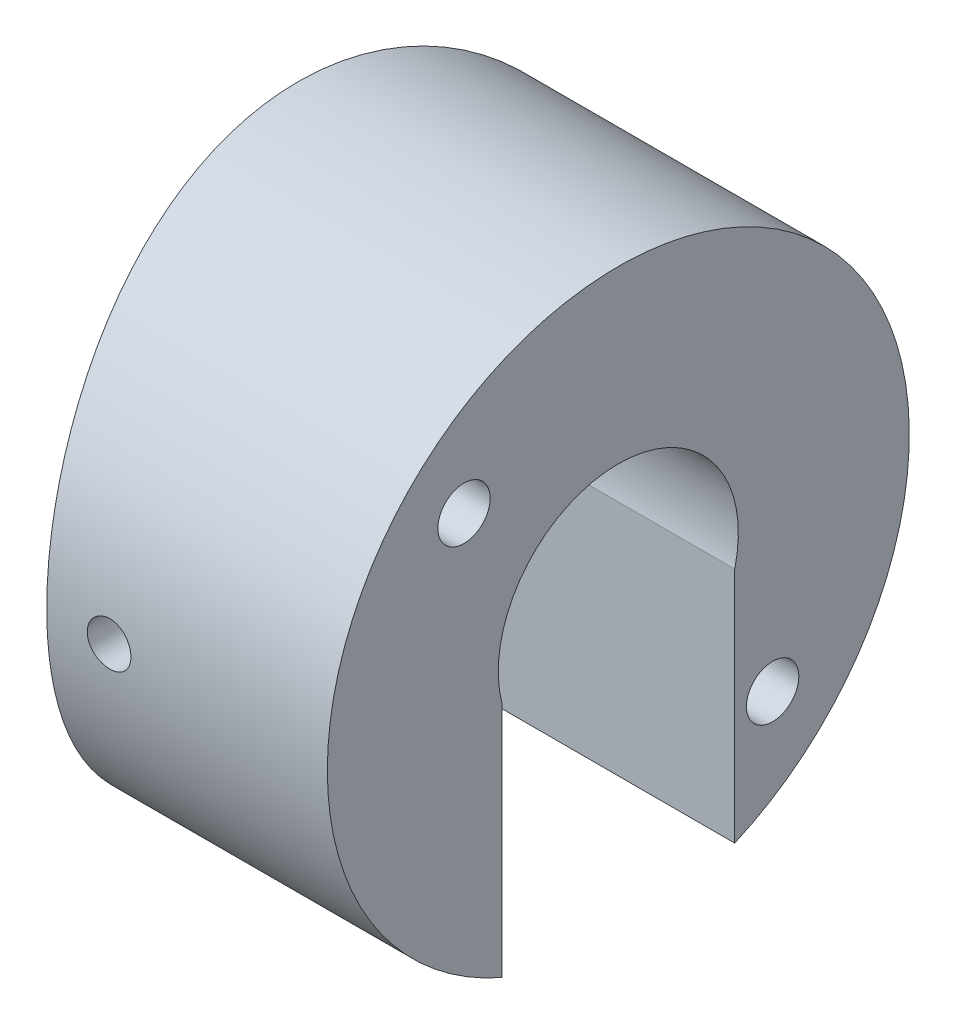
SolidWorks part; units mm, degrees
ref_plane "Plano frontal" through (0, 0, 0) normal (0, 0, 1) x (1, 0, 0)
ref_plane "Plano superior" through (0, 0, 0) normal (0, 1, 0) x (1, 0, 0)
ref_plane "Plano direito" through (0, 0, 0) normal (1, 0, 0) x (0, 0, -1)
sketch "Sketch1" plane through (0, 0, 0) normal (1, 0, 0) x (0, 0, -1)
  circle A0 centre (0, 0) radius 20
  dimension "D1" = 40
extrude "Bloco" add sketch "Sketch1" along normal blind 22
sketch "Sketch2" plane through (22, 0, 0) normal (1, 0, 0) x (0, 0, -1)
  line L0 (-8, -18.3303) -> (-8, -2.0156)
  line L1 (8, -2.0156) -> (8, -18.3303)
  arc A0 (8, -2.0156) -> (-8, -2.0156) centre (0, 0) ccw
  circle A1 centre (0, 0) radius 20 construction
  arc A2 (-8, -18.3303) -> (8, -18.3303) centre (0, 0) ccw
  dimension "D1" = 16.5
  dimension "D2" = 8
  dimension "D3" = 16
extrude "Encaixe do Potenciômetro" cut sketch "Sketch2" against normal blind 18
hole_wizard "Furo de Fixação - Parafuso M3" positions "Sketch5" profile "Sketch6" counterbore size "M3" standard "ANSI Metric" end condition up to next
sketch "Sketch5" plane through (0, 0, 0) normal (-1, 0, 0) x (0, 0, 1)
  line L0 (0, 0) -> (-10.6066, -10.6066) construction
  line L2 (0, 0) -> (10.6066, 10.6066) construction
  line L4 (20, 0) -> (-20, 0) construction
  circle A0 centre (0, 0) radius 20 construction
  point P18 (-10.6066, -10.6066)
  point P22 (10.6066, 10.6066)
  point P38 (-11.9873, -9.017)
  dimension "D1" = 45
  dimension "D2" = 15
  dimension "D3" = 30
sketch "Sketch6" plane through (0, 10.6066, 10.6066) normal (0, 1, 0) x (0, 0, 1)
  line L0 (0, 0) -> (0, 22)
  line L1 (0, 22) -> (1.8, 22)
  line L3 (1.8, 22) -> (1.8, 3)
  line L4 (1.8, 3) -> (3.25, 3)
  line L5 (3.25, 3) -> (3.25, 0)
  line L7 (3.25, 0) -> (0, 0)
  line L11 (0, -6.35) -> (0, 107.95) construction
  dimension "Thru Hole Dia." = 3.6
  dimension "Thru Hole Depth" = 22
  dimension "C'Bore Dia." = 6.5
  dimension "C'Bore Depth" = 3
sketch "Sketch7" plane through (0, 0, 0) normal (0, 1, 0) x (1, 0, 0)
  circle A0 centre (75, 0) radius 75
  circle A1 centre (75, 0) radius 100
  dimension "D2" = 200
  dimension "D1" = 75
extrude "Corte - Arredondamento" cut sketch "Sketch7" against normal through all and the other way through all
sketch "Sketch8" plane through (0, 0, 0) normal (0, 0, 1) x (1, 0, 0)
  line L0 (22, -18.3303) -> (22, 20) construction
  line L1 (0, 0) -> (7, 0) construction
  circle A0 centre (7, 0) radius 1.5
  dimension "D1" = 3
  dimension "D2" = 15
extrude "Furo de Fixação - Potenciômetro" cut sketch "Sketch8" along normal up to next
